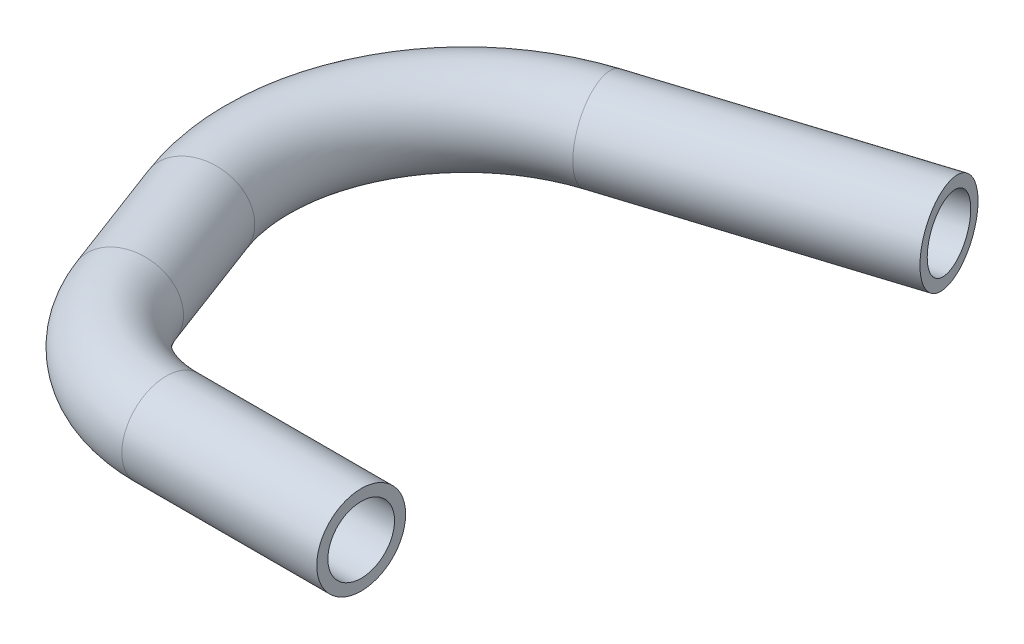
SolidWorks part; units mm, degrees
material "Silicon Rubber"
ref_plane "Plano frontal" through (0, 0, 0) normal (0, 0, 1) x (1, 0, 0)
ref_plane "Plano superior" through (0, 0, 0) normal (0, 1, 0) x (1, 0, 0)
ref_plane "Plano direito" through (0, 0, 0) normal (1, 0, 0) x (0, 0, -1)
sketch "Sketch1" plane through (0, 0, 0) normal (0, 1, 0) x (1, 0, 0)
  line L0 (-70.197, 0) -> (0, 0)
  line L1 (-116.9925, 32.3881) -> (-132.4963, 73.5821)
  line L2 (-84.8559, 171.5288) -> (10.197, 201.4988)
  line L3 (0, -110.8244) -> (0, 110.8244) construction
  line L4 (84.8559, 171.5288) -> (-10.197, 201.4988) construction
  line L5 (116.9925, 32.3881) -> (132.4963, 73.5821) construction
  line L6 (-116.9925, 32.3881) -> (-104.803, 0) construction
  line L7 (-104.803, 0) -> (-70.197, 0) construction
  arc A0 (-132.4963, 73.5821) -> (-84.8559, 171.5288) centre (-62.303, 100) cw
  arc A1 (-116.9925, 32.3881) -> (-70.197, 0) centre (-70.197, 50) ccw
  arc A2 (116.9925, 32.3881) -> (70.197, 0) centre (70.197, 50) cw construction
  arc A3 (132.4963, 73.5821) -> (84.8559, 171.5288) centre (62.303, 100) ccw construction
  point P0 (70.197, 0)
  point P17 (0, 0)
  dimension "D4" = 50
  dimension "D6" = 50
  dimension "D5" = 75
  dimension "D8" = 62.303
  dimension "D1" = 42.5
  dimension "D2" = 115
  dimension "D3" = 201.4988
  dimension "D7" = 70.197
  dimension "D9" = 145
sketch "Sketch2" plane through (0, 0, 0) normal (1, 0, 0) x (0, 0, -1)
  circle A0 centre (0, 0) radius 12
  circle A1 centre (0, 0) radius 16
  dimension "D1" = 24
  dimension "D2" = 32
sweep "Sweep1" add profiles "Sketch2" path "Sketch1"
